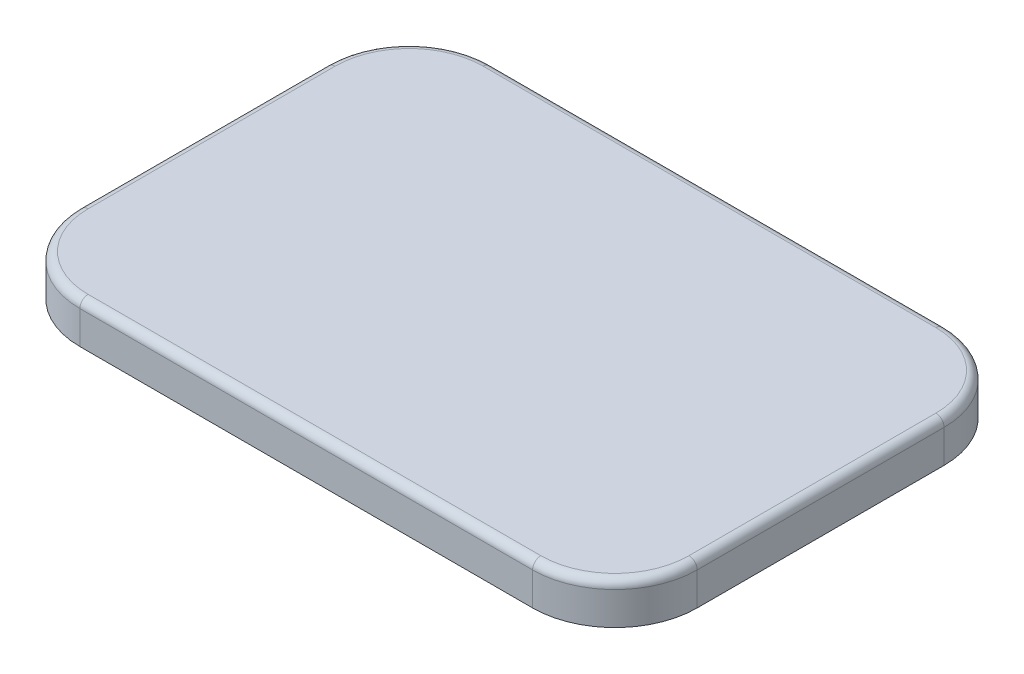
SolidWorks part; units mm, degrees
ref_plane "Front Plane" through (0, 0, 0) normal (0, 0, 1) x (1, 0, 0)
ref_plane "Top Plane" through (0, 0, 0) normal (0, 1, 0) x (1, 0, 0)
ref_plane "Right Plane" through (0, 0, 0) normal (1, 0, 0) x (0, 0, -1)
sketch "Sketch2" plane through (0, 0, 0) normal (0, 1, 0) x (1, 0, 0)
  line L1 (55, -50) -> (-55, -50)
  line L2 (75, -30) -> (75, 30)
  line L3 (55, 50) -> (-55, 50)
  line L4 (-75, -30) -> (-75, 30)
  line L5 (75, -50) -> (-75, 50) construction
  line L6 (75, 50) -> (-75, -50) construction
  arc A0 (-55, -50) -> (-75, -30) centre (-55, -30) cw
  arc A1 (75, 30) -> (55, 50) centre (55, 30) ccw
  arc A2 (55, -50) -> (75, -30) centre (55, -30) ccw
  arc A3 (-55, 50) -> (-75, 30) centre (-55, 30) ccw
  point P0 (0, 0)
  dimension "D3" = 20
  dimension "D1" = 150
  dimension "D2" = 100
extrude "Boss-Extrude1" add sketch "Sketch2" along normal blind 10
fillet "Fillet1" radius 2 8 edges at (-75, 10, 0) (-69.1421, 10, -44.1421) (0, 10, -50) (69.1421, 10, -44.1421) (75, 10, 0) (69.1421, 10, 44.1421) (0, 10, 50) (-69.1421, 10, 44.1421)
